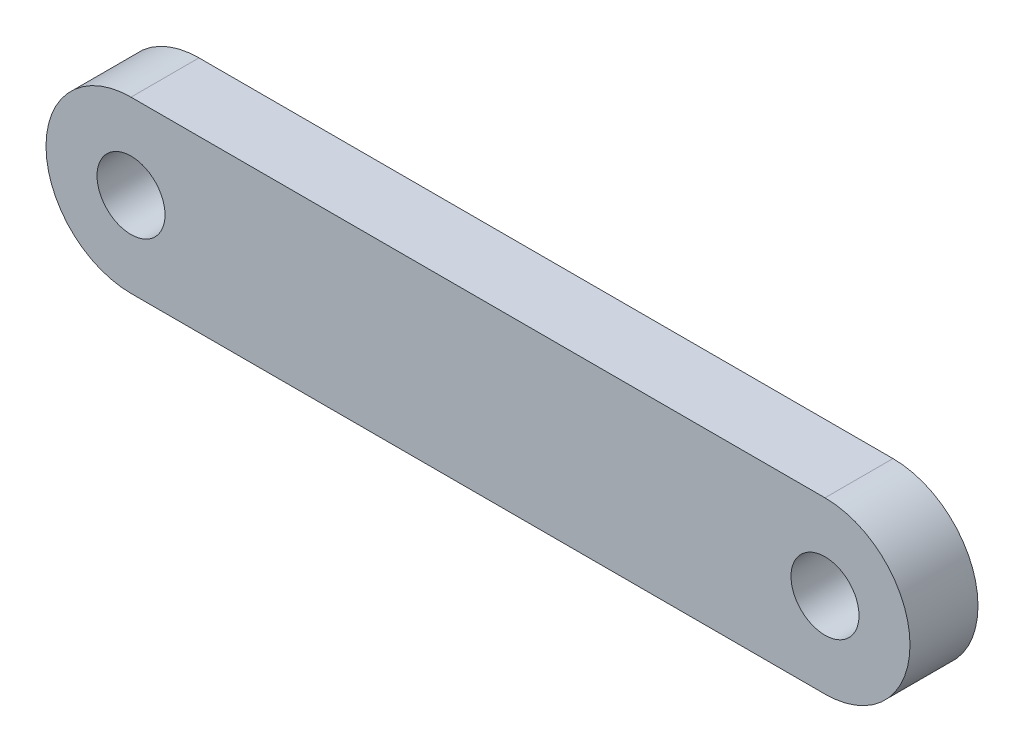
SolidWorks part; units mm, degrees
material "ABS"
ref_plane "Front Plane" through (0, 0, 0) normal (0, 0, 1) x (1, 0, 0)
ref_plane "Top Plane" through (0, 0, 0) normal (0, 1, 0) x (1, 0, 0)
ref_plane "Right Plane" through (0, 0, 0) normal (1, 0, 0) x (0, 0, -1)
sketch "Sketch1" plane through (0, 0, 0) normal (0, 0, 1) x (1, 0, 0)
  line L0 (0, 3.175) -> (25.9207, 3.175)
  line L1 (0, -3.175) -> (25.9207, -3.175)
  circle A0 centre (0, 0) radius 1.27
  circle A1 centre (0, 0) radius 3.175
  circle A2 centre (25.9207, 0) radius 1.27
  circle A3 centre (25.9207, 0) radius 3.175
  dimension "D1" = 2.54
  dimension "D2" = 6.35
  dimension "D3" = 25.9207
extrude "Boss-Extrude2" add sketch "Sketch1" along normal blind 2.54 contours A1 A0 | A3 A2 | A3 L0 A1 L1
